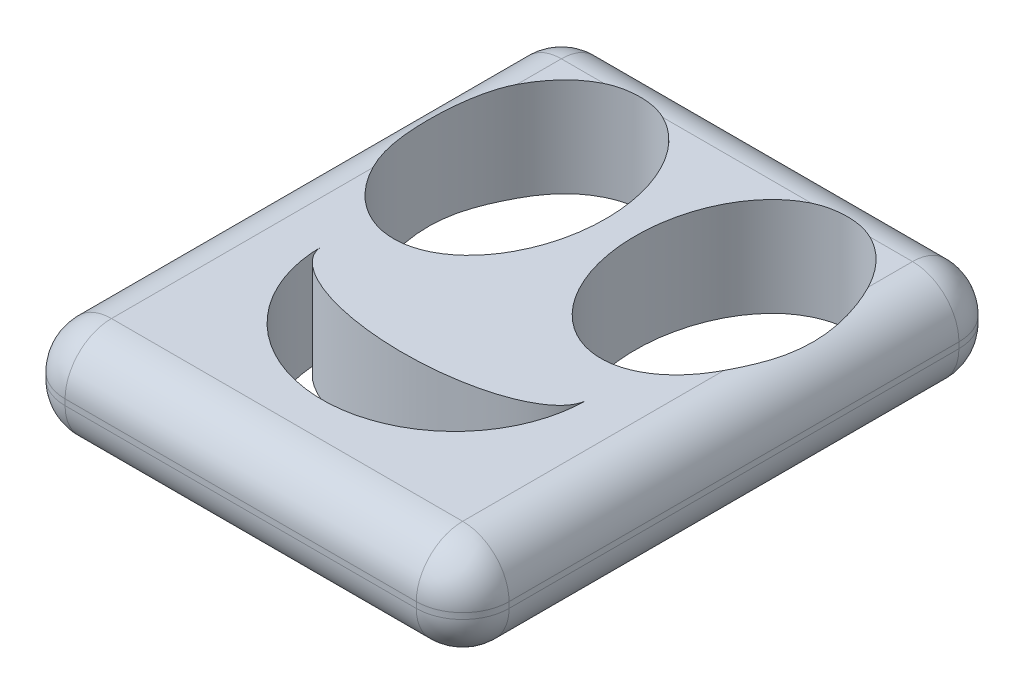
SolidWorks part; units mm, degrees
ref_plane "Piano frontale" through (0, 0, 0) normal (0, 0, 1) x (1, 0, 0)
ref_plane "Piano superiore" through (0, 0, 0) normal (0, 1, 0) x (1, 0, 0)
ref_plane "Piano destro" through (0, 0, 0) normal (1, 0, 0) x (0, 0, -1)
sketch "Schizzo1" plane through (0, 0, 0) normal (0, 1, 0) x (1, 0, 0)
  line L1 (-22.5, -27.5) -> (22.5, -27.5)
  line L2 (-22.5, -27.5) -> (-22.5, 27.5)
  line L3 (-22.5, 27.5) -> (22.5, 27.5)
  line L4 (22.5, -27.5) -> (22.5, 27.5)
  line L5 (-22.5, -27.5) -> (22.5, 27.5) construction
  line L6 (-22.5, 27.5) -> (22.5, -27.5) construction
  point P0 (0, 0)
  dimension "D1" = 45
  dimension "D2" = 55
extrude "Estrusione-Estrusione1" add sketch "Schizzo1" along normal blind 10
fillet "Raccordo1" radius 4.7 12 edges at (0, 10, -27.5) (0, 0, -27.5) (-22.5, 5, -27.5) (-22.5, 10, 0) (-22.5, 0, 0) (-22.5, 5, 27.5) (0, 10, 27.5) (0, 0, 27.5) (22.5, 5, 27.5) (22.5, 10, 0) (22.5, 5, -27.5) (22.5, 0, 0)
sketch "Schizzo3" plane through (0, 10, 0) normal (0, 1, 0) x (1, 0, 0)
  line L0 (0, 32.0626) -> (0, -31.5395) construction
  ellipse E0 centre (-10.5, 11) end of major axis (-10.5, -1.5) minor radius 9
  ellipse E1 centre (10.5, 11) end of major axis (10.5, -1.5) minor radius 9
  dimension "D1" = 18
  dimension "D2" = 25
sketch "Schizzo4" plane through (0, 10, 0) normal (0, 1, 0) x (1, 0, 0)
  line L0 (-53.1058, 0) -> (41.7751, 0) construction
  arc A1 (13.4602, -5.7935) -> (-13.4602, -5.7935) centre (0, -5.7935) cw
  ellipse E0 centre (0, -5.7935) end of major axis (-13.4602, -5.7935) minor radius 5.2534 (13.4602, -5.7935) -> (-13.4602, -5.7935) cw
extrude "Taglio-Estrusione3" cut sketch "Schizzo3" against normal blind 20 and the other way blind 20
extrude "Taglio-Estrusione4" cut sketch "Schizzo4" against normal blind 20
